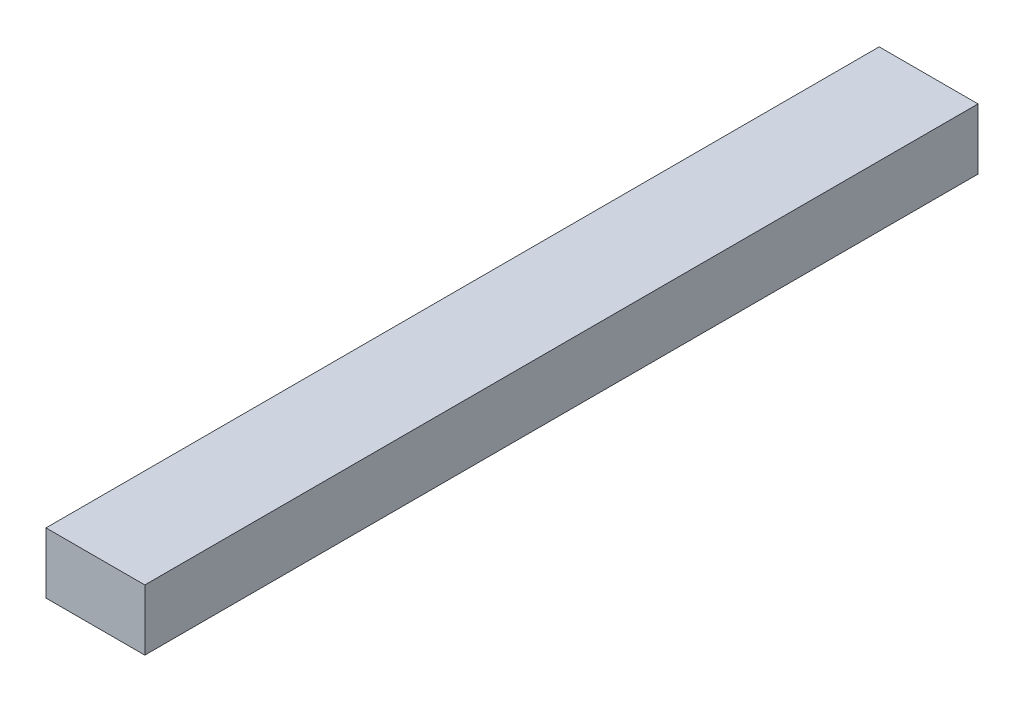
SolidWorks part; units mm, degrees
ref_plane "Front Plane" through (0, 0, 0) normal (0, 0, 1) x (1, 0, 0)
ref_plane "Top Plane" through (0, 0, 0) normal (0, 1, 0) x (1, 0, 0)
ref_plane "Right Plane" through (0, 0, 0) normal (1, 0, 0) x (0, 0, -1)
sketch "Sketch1" plane through (0, 0, 0) normal (0, 0, 1) x (1, 0, 0)
  line L1 (-13.5927, 7.3372) -> (16.5317, 7.3372)
  line L2 (-13.5927, 7.3372) -> (-13.5927, -11.2048)
  line L3 (-13.5927, -11.2048) -> (16.5317, -11.2048)
  line L4 (16.5317, 7.3372) -> (16.5317, -11.2048)
  dimension "D1" = 30.1244
  dimension "D2" = 18.542
extrude "Boss-Extrude1" add sketch "Sketch1" along normal blind 254 contours L2 L3 L4 L1
